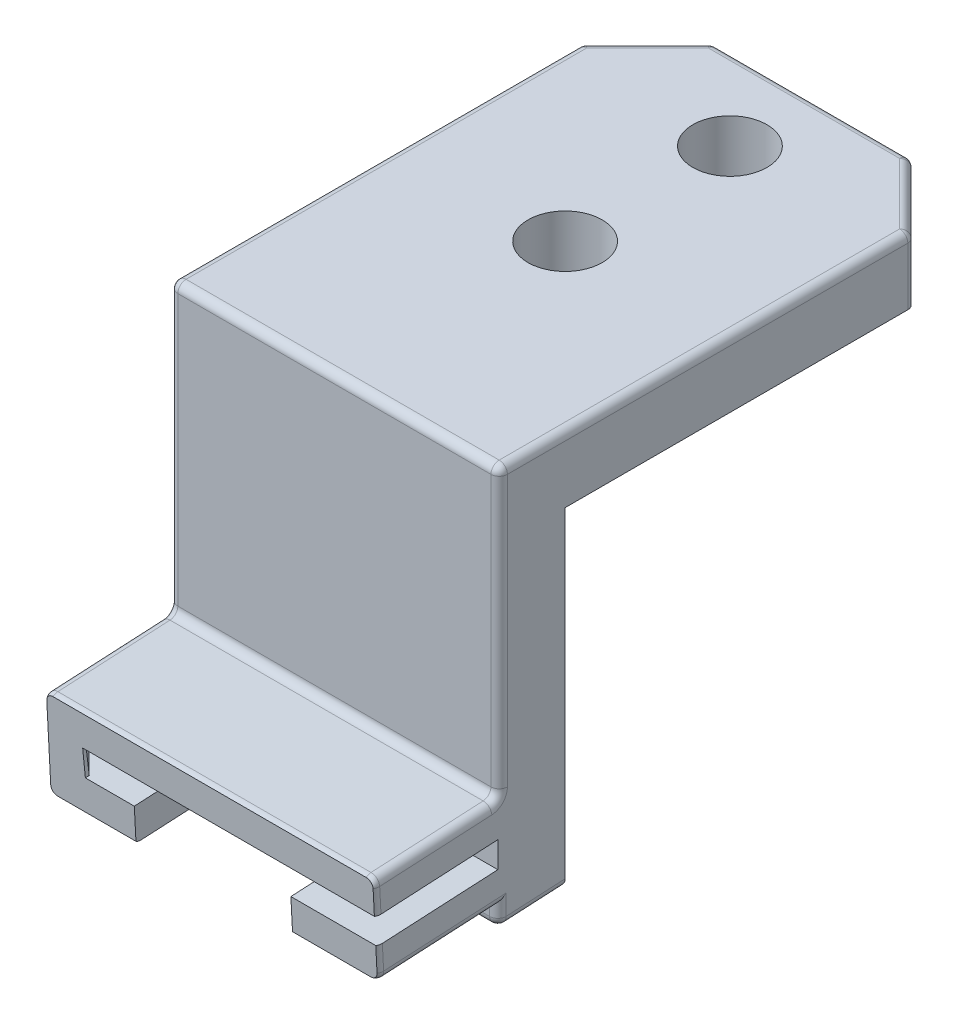
SolidWorks part; units mm, degrees
ref_plane "Front Plane" through (0, 0, 0) normal (0, 0, 1) x (1, 0, 0)
ref_plane "Top Plane" through (0, 0, 0) normal (0, 1, 0) x (1, 0, 0)
ref_plane "Right Plane" through (0, 0, 0) normal (1, 0, 0) x (0, 0, -1)
sketch "Sketch1" plane through (0, 0, 0) normal (0, 1, 0) x (1, 0, 0)
  line L0 (0, 0) -> (0, 50000) construction
  line L1 (-12.7, -15.875) -> (12.7, -15.875)
  line L2 (-12.7, -15.875) -> (-12.7, 15.875)
  line L3 (-12.7, 15.875) -> (12.7, 15.875)
  line L4 (12.7, -15.875) -> (12.7, 15.875)
  line L5 (-12.7, -15.875) -> (12.7, 15.875) construction
  line L6 (-12.7, 15.875) -> (12.7, -15.875) construction
  circle A0 centre (0, 9.525) radius 2.8575
  circle A1 centre (0, -3.175) radius 2.8575
  point P0 (0, 0)
  dimension "D4" = 5.715
  dimension "D1" = 25.4
  dimension "D2" = 31.75
  dimension "D3" = 12.7
  dimension "D5" = 25.4
extrude "Boss-Extrude1" add sketch "Sketch1" along normal blind 5.08
sketch "Sketch2" plane through (0, 0, 0) normal (1, 0, 0) x (0, 0, -1)
  line L0 (-20.955, -21.5606) -> (-15.875, -21.2944) construction
  line L1 (-15.875, 5.08) -> (-20.955, 5.08)
  line L2 (-15.875, 5.08) -> (-15.875, -25.4)
  line L3 (-15.875, -25.4) -> (-25.4558, -25.9021) construction
  line L4 (-30.6984, -20.0685) -> (-30.5938, -22.0658)
  line L5 (-15.875, 0) -> (15.875, 0) construction
  line L6 (-21.0597, -19.5633) -> (-15.875, -19.2916) construction
  line L7 (-20.955, 5.08) -> (-20.955, -17.0144)
  line L8 (-21.0597, -25.6717) -> (-15.875, -25.4)
  line L9 (-20.955, -17.0144) -> (-30.8314, -17.532)
  line L10 (-30.8314, -17.532) -> (-30.4608, -24.6023)
  line L11 (-30.4608, -24.6023) -> (-21.0597, -24.1096)
  line L13 (-20.955, -21.5606) -> (-21.0597, -19.5633) construction
  line L14 (-30.6984, -20.0685) -> (-21.0597, -19.5633)
  line L15 (-30.5938, -22.0658) -> (-21.0597, -21.5661)
  line L16 (-21.0597, -19.5633) -> (-21.0597, -21.5661)
  line L17 (-21.0597, -21.5661) -> (-20.955, -21.5606) construction
  line L18 (-21.0597, -24.1096) -> (-21.0597, -25.6717)
  point P14 (-20.955, -21.5606)
  point P18 (-21.5343, -25.6966)
  dimension "D1" = 25.4
  dimension "D2" = 87
  dimension "D4" = 4.1
  dimension "D5" = 5.08
  dimension "D6" = 9.652
  dimension "D3" = 2
  dimension "D7" = 2.54
  dimension "D9" = 2.54
  dimension "D8" = 3
extrude "Boss-Extrude2" add sketch "Sketch2" along normal up to surface and the other way up to surface contours L4 L15 L13 L14 | L11 L18 L8 L2 L1 L7 L9 L10 L15 L4 L14 L13 up to face at (12.7, 2.54, 0) other way up to face at (-12.7, 2.54, 0)
sketch "Sketch4" plane through (0, -1.6594, 31.6632) normal (0, -0.0523, 0.9986) x (1, 0, 0)
  line L0 (0, -18.4344) -> (0, -20.4344) construction
  line L1 (0, -18.4344) -> (0, -20.4344) construction
  line L2 (12.7, -24.5344) -> (-12.7, -24.5344) construction
  line L3 (-11.43, -20.4344) -> (-6.0325, -20.4344)
  line L4 (-11.43, -20.4344) -> (-11.43, -18.4344)
  line L5 (-11.43, -18.4344) -> (12.7, -18.4344)
  line L6 (12.7, -20.4344) -> (12.7, -18.4344)
  line L7 (12.7, -22.9744) -> (12.7, -15.8944) construction
  line L8 (12.7, -22.9744) -> (-12.7, -22.9744) construction
  line L10 (-6.0325, -20.4344) -> (-6.0325, -22.9744)
  line L11 (-6.0325, -22.9744) -> (6.0325, -22.9744)
  line L12 (6.0325, -20.4344) -> (6.0325, -22.9744)
  line L13 (6.0325, -20.4344) -> (12.7, -20.4344)
  point P16 (0, -24.5344)
  point P17 (0, -22.9744)
  dimension "D1" = 11.43
  dimension "D2" = 12.065
extrude "Cut-Extrude3" cut sketch "Sketch4" against normal up to surface (9.5472 mm away)
sketch "Sketch5" plane through (0, -18.4091, -0.9648) normal (0, -0.9986, -0.0523) x (1, 0, 0)
  line L13 (-9.906, 31.7067) -> (-9.398, 31.7067) construction
  line L14 (-11.43, 22.0547) -> (-11.43, 31.7067) construction
  line L15 (12.7, 31.7067) -> (-11.43, 31.7067) construction
  line L16 (-9.398, 31.7067) -> (-9.906, 31.1987) construction
  line L17 (-9.906, 31.1987) -> (-9.906, 31.7067)
  line L18 (-11.43, 31.7067) -> (-9.906, 31.7067)
  line L19 (-11.43, 29.6747) -> (-11.43, 31.7067)
  line L20 (-9.906, 31.1987) -> (-11.43, 29.6747)
  point P2 (9.25, 33.7947)
  point P3 (9.25, 33.7947)
  point P6 (0, 0)
  point P7 (9.1827, 33.1668)
  point P18 (0, 31.7067)
  point P19 (0, 0)
  point P21 (0, 0)
  line M3 (12.7, 31.7067) -> (-11.43, 31.7067)
  line M4 (-11.43, 31.7067) -> (-11.43, 22.0547)
  dimension "D1" = 9.906
  dimension "D2" = 135
  dimension "D3" = 2.032
extrude "Boss-Extrude3" add sketch "Sketch5" along normal up to surface (2 mm away) draft 3 contours L20 L17 M3 M4
chamfer "Chamfer1" distance 5.08 angle 45 2 edges at (-12.7, 2.54, -15.875) (12.7, 2.54, -15.875)
fillet "Fillet1" radius 0.635 28 edges at (12.7, -5.9672, 20.955) (0, 5.08, 20.955) (12.7, -25.5359, 18.4673) (0, -25.6717, 21.0597) (12.7, -24.8906, 21.0597) (12.7, -24.3559, 25.7603) (9.3663, -24.6023, 30.4608) (12.7, -23.334, 30.5273) (0, -17.532, 30.8314) (12.7, -17.2732, 25.8932) (0, -17.0144, 20.955) (-12.7, -17.2732, 25.8932) (-12.7, -5.9672, 20.955) (-12.7, -25.5359, 18.4673) (-12.7, -24.8906, 21.0597) (-12.7, -24.3559, 25.7603) (-12.7, -21.0671, 30.6461) (-9.3663, -24.6023, 30.4608) (12.7, -18.8002, 30.7649) (12.7, 5.08, 5.08) (-12.7, 5.08, 5.08) (-12.7, 2.54, -10.795) (0, 5.08, -15.875) (7.62, 2.54, -15.875) (-7.62, 2.54, -15.875) (10.16, 5.08, -13.335) (-10.16, 5.08, -13.335) (12.7, 2.54, -10.795)
sketch "Sketch8" plane through (0, -15.8726, -0.8318) normal (0, 0.9986, 0.0523) x (1, 0, 0)
  line L1 (-12.7, -31.4527) -> (12.7, -31.4527)
  line L2 (-12.7, -31.4527) -> (-12.7, -37.8027)
  line L3 (-12.7, -37.8027) -> (12.7, -37.8027)
  line L4 (12.7, -31.4527) -> (12.7, -37.8027)
  dimension "D1" = 6.35
extrude "Cut-Extrude4" cut sketch "Sketch8" against normal through all
equation "\"D1@Sketch1\"=1in"
equation "\"D5@Sketch1\"=1in"
equation "\"D2@Sketch1\"=1.25in"
equation "\"D3@Sketch1\"=.5in"
equation "\"D4@Sketch1\"=.225in"
equation "\"D5@Sketch2\"=.2in"
equation "\"D1@Sketch2\"=1in"
equation "\"D6@Sketch2\"=0.38in"
equation "\"D9@Sketch2\"=.1in"
equation "\"D7@Sketch2\"=.1in"
equation "\"D3@Sketch2\"=.2cm"
equation "\"D4@Sketch2\"=.41cm"
